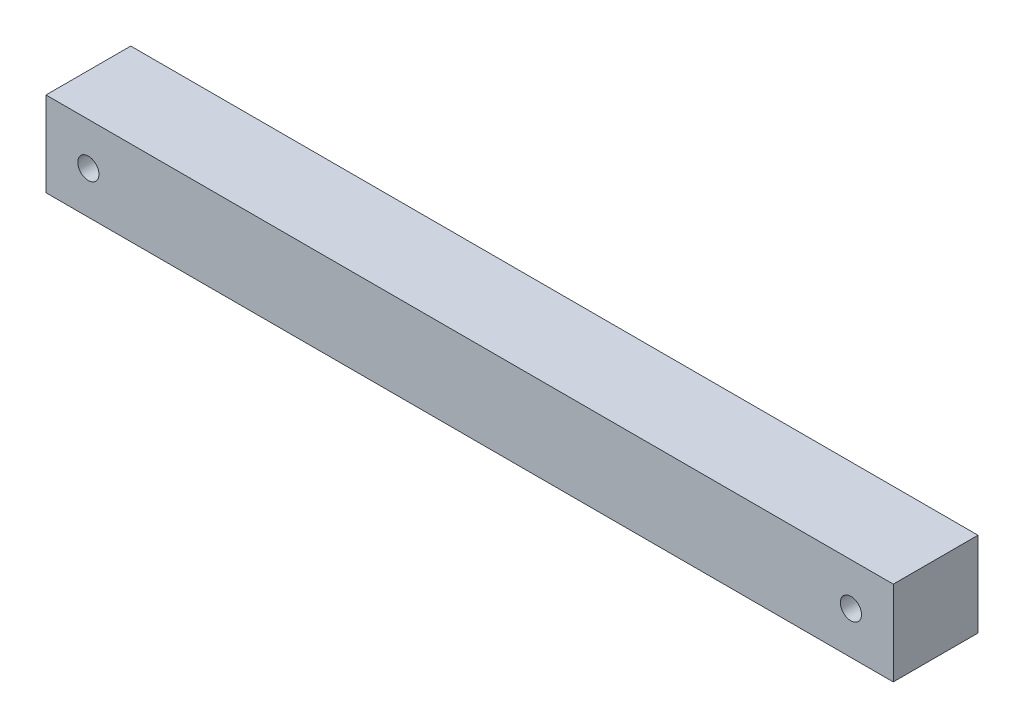
SolidWorks part; units mm, degrees
ref_plane "Front" through (0, 0, 0) normal (0, 0, 1) x (1, 0, 0)
ref_plane "Top" through (0, 0, 0) normal (0, 1, 0) x (1, 0, 0)
ref_plane "Right" through (0, 0, 0) normal (1, 0, 0) x (0, 0, -1)
sketch "Sketch1" plane through (0, 0, 0) normal (0, 0, 1) x (1, 0, 0)
  line L0 (3658.0105, 341.0022) -> (3912.0105, 341.0022) construction
  line L1 (3658.0105, 353.7022) -> (3912.0105, 353.7022)
  line L2 (3658.0105, 353.7022) -> (3658.0105, 328.3022)
  line L3 (3658.0105, 328.3022) -> (3912.0105, 328.3022)
  line L4 (3912.0105, 353.7022) -> (3912.0105, 328.3022)
  line L5 (3785.0105, 353.7022) -> (3785.0105, 328.3022) construction
  circle A0 centre (3670.7105, 341.0022) radius 3.175
  circle A1 centre (3899.3105, 341.0022) radius 3.175
  dimension "D3" = 6.35
  dimension "D1" = 25.4
  dimension "D2" = 254
  dimension "D4" = 114.3
extrude "Extrude1" add sketch "Sketch1" along normal mid plane 25.4
